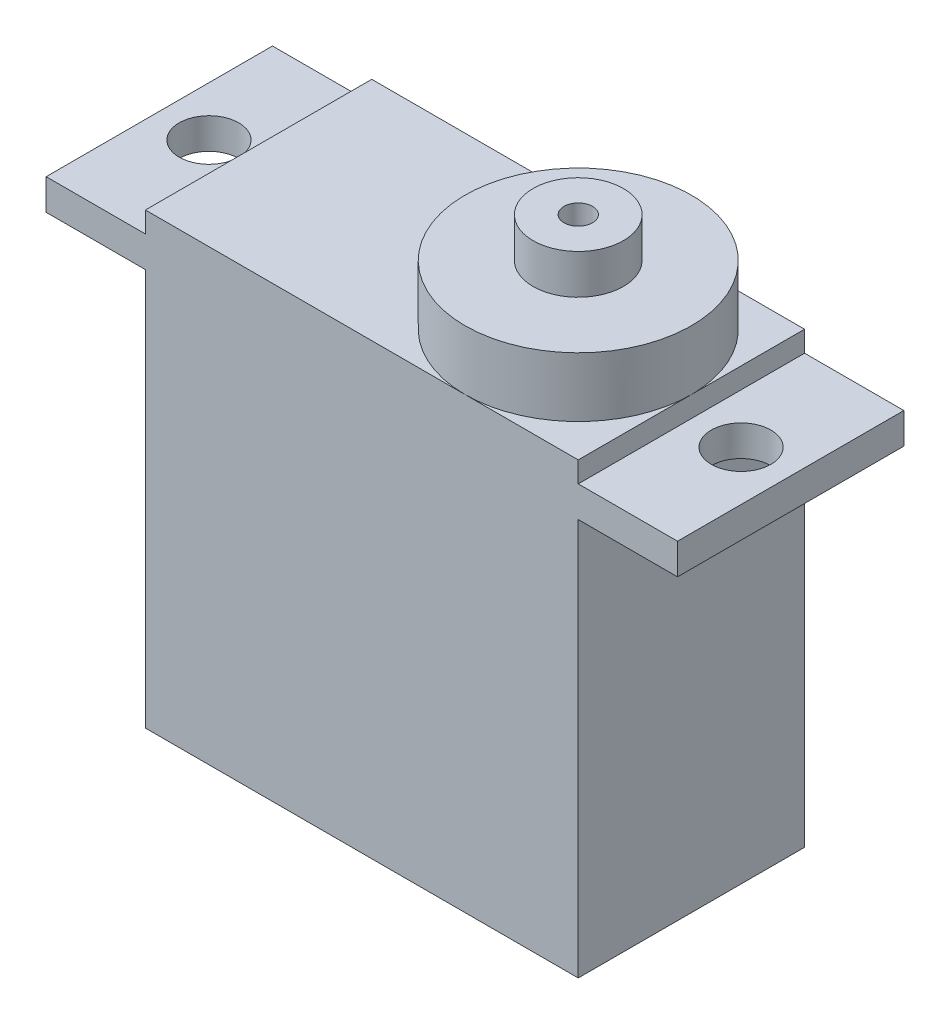
SolidWorks part; units mm, degrees
ref_plane "Ön Düzlem" through (0, 0, 0) normal (0, 0, 1) x (1, 0, 0)
ref_plane "Üst Düzlem" through (0, 0, 0) normal (0, 1, 0) x (1, 0, 0)
ref_plane "Sağ Düzlem" through (0, 0, 0) normal (1, 0, 0) x (0, 0, -1)
sketch "Sketch1" plane through (0, 0, 0) normal (0, 0, 1) x (1, 0, 0)
  line L1 (-10.9, 11.3) -> (10.9, 11.3)
  line L2 (-10.9, 11.3) -> (-10.9, -11.3)
  line L3 (-10.9, -11.3) -> (10.9, -11.3)
  line L4 (10.9, 11.3) -> (10.9, -11.3)
  line L5 (-10.9, 11.3) -> (10.9, -11.3) construction
  line L6 (-10.9, -11.3) -> (10.9, 11.3) construction
  point P0 (0, 0)
  dimension "D1" = 10.9
  dimension "D2" = 11.3
extrude "Boss-Extrude1" add sketch "Sketch1" along normal blind 11.4
sketch "Sketch2" plane through (0, 0, 11.4) normal (0, 0, 1) x (1, 0, 0)
  line L1 (10.9, -11.3) -> (10.9, 11.3) construction
  line L2 (10.9, 11.3) -> (-10.9, 11.3) construction
  line L8 (-15.9, 10.2529) -> (15.9, 8.6973) construction
  line L9 (15.9, 10.2529) -> (15.9, 8.6973)
  line L10 (-15.9, 10.2529) -> (15.9, 10.2529)
  line L11 (-15.9, 8.6973) -> (15.9, 8.6973)
  line L12 (-15.9, 8.6973) -> (15.9, 10.2529) construction
  line L13 (-15.9, 10.2529) -> (-15.9, 8.6973)
  point P5 (0, 9.4751)
  dimension "D1" = 5
  dimension "D2" = 10.9
  dimension "D3" = 1.0471
  dimension "D4" = 1.8249
extrude "Boss-Extrude2" add sketch "Sketch2" against normal up to surface (11.4 mm away) up to face at (0, 0, 0)
sketch "Sketch3" plane through (0, 11.3, 0) normal (0, 1, 0) x (1, 0, 0)
  circle A0 centre (5.2, -5.7) radius 5.7
extrude "Boss-Extrude3" add sketch "Sketch3" along normal blind 3
sketch "Sketch4" plane through (0, 14.3, 0) normal (0, 1, 0) x (1, 0, 0)
  circle A0 centre (5.2, -5.7) radius 2.275
extrude "Boss-Extrude4" add sketch "Sketch4" along normal blind 2
sketch "Sketch5" plane through (0, 16.3, 0) normal (0, 1, 0) x (1, 0, 0)
  circle A0 centre (5.2, -5.7) radius 0.7178
extrude "Cut-Extrude1" cut sketch "Sketch5" against normal blind 2.4
sketch "Sketch7" plane through (0, 10.2529, 0) normal (0, 1, 0) x (1, 0, 0)
  circle A2 centre (13.4, -5.699) radius 1.5
  circle A4 centre (-13.4, -5.7) radius 1.5
extrude "Cut-Extrude2" cut sketch "Sketch7" against normal blind 10 contours A2 | A4
